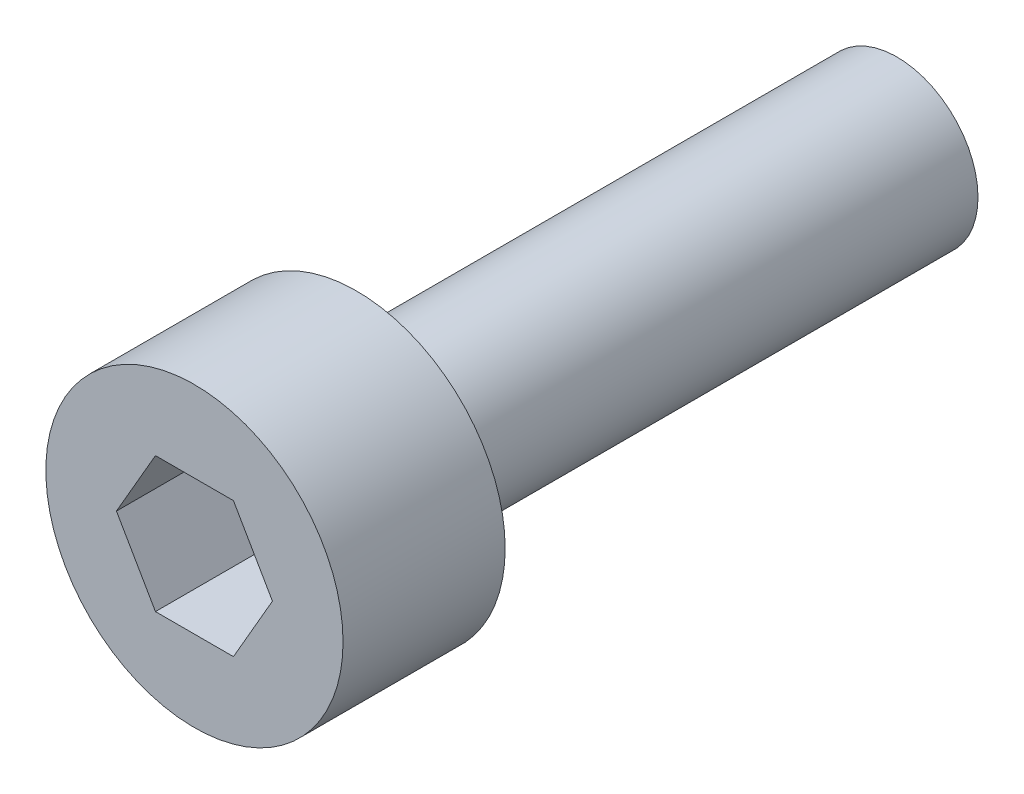
SolidWorks part; units mm, degrees
ref_plane "Plan de face" through (0, 0, 0) normal (0, 0, 1) x (1, 0, 0)
ref_plane "Plan de dessus" through (0, 0, 0) normal (0, 1, 0) x (1, 0, 0)
ref_plane "Plan de droite" through (0, 0, 0) normal (1, 0, 0) x (0, 0, -1)
sketch "Esquisse1" plane through (0, 0, 0) normal (0, 0, 1) x (1, 0, 0)
  circle A0 centre (0, 0) radius 1.5
  dimension "D1" = 3
extrude "Boss.-Extru.1" add sketch "Esquisse1" along normal blind 10
sketch "Esquisse2" plane through (0, 0, 10) normal (0, 0, 1) x (1, 0, 0)
  circle A0 centre (0, 0) radius 2.75
  dimension "D1" = 5.5
extrude "Boss.-Extru.2" add sketch "Esquisse2" along normal blind 3
sketch "Esquisse3" plane through (0, 0, 13) normal (0, 0, 1) x (1, 0, 0)
  line L1 (1.4434, 0) -> (0.7217, 1.25)
  line L2 (0.7217, 1.25) -> (-0.7217, 1.25)
  line L3 (-0.7217, 1.25) -> (-1.4434, 0)
  line L4 (-1.4434, 0) -> (-0.7217, -1.25)
  line L5 (-0.7217, -1.25) -> (0.7217, -1.25)
  line L6 (0.7217, -1.25) -> (1.4434, 0)
  circle A0 centre (0, 0) radius 1.25 construction
  dimension "D1" = 2.5
extrude "Enlèv. mat.-Extru.1" cut sketch "Esquisse3" against normal blind 2
